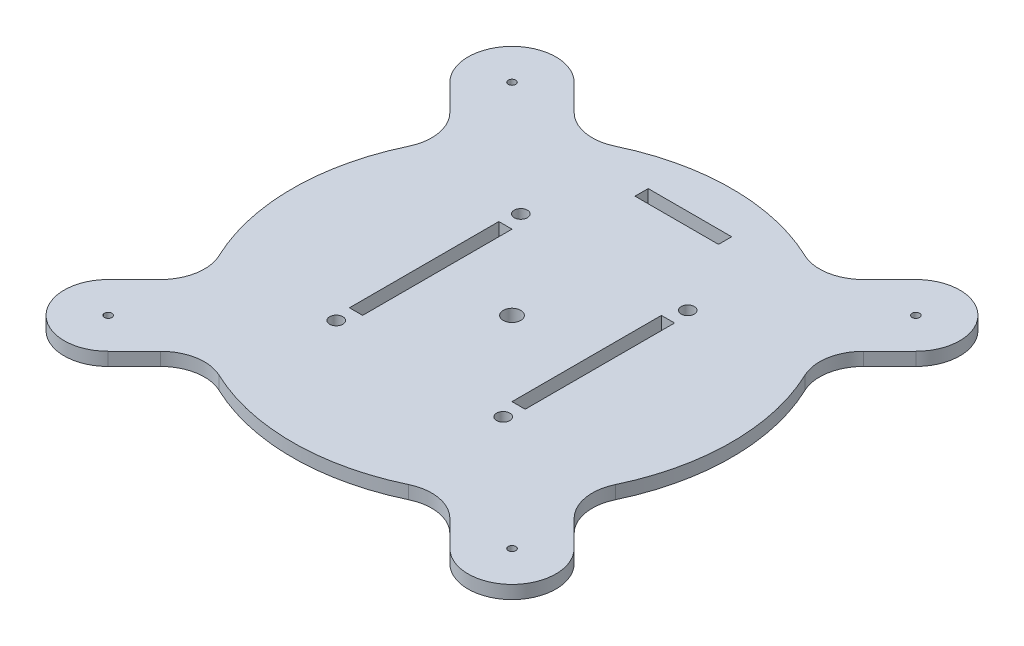
SolidWorks part; units mm, degrees
ref_plane "Plan de face" through (0, 0, 0) normal (0, 0, 1) x (1, 0, 0)
ref_plane "Plan de dessus" through (0, 0, 0) normal (0, 1, 0) x (1, 0, 0)
ref_plane "Plan de droite" through (0, 0, 0) normal (1, 0, 0) x (0, 0, -1)
sketch "Esquisse1" plane through (0, 0, 0) normal (0, 1, 0) x (1, 0, 0)
  line L0 (-45.9619, -45.9619) -> (0, 0) construction
  line L1 (0, 0) -> (-75, 0) construction
  line L2 (-45.9619, -45.9619) -> (-53.033, -53.033) construction
  line L3 (0, 0) -> (0, 75) construction
  line L4 (-38.8909, -53.033) -> (-27.5699, -41.7121)
  line L5 (-53.033, -38.8909) -> (-41.7121, -27.5699)
  line L6 (-38.8909, 53.033) -> (-27.5699, 41.7121)
  line L7 (-41.7121, 27.5699) -> (-53.033, 38.8909)
  line L8 (0, 0) -> (-45.9619, 45.9619) construction
  line L9 (0, 0) -> (45.9619, 45.9619) construction
  line L10 (0, 0) -> (45.9619, -45.9619) construction
  line L11 (27.5699, 41.7121) -> (38.8909, 53.033)
  line L12 (41.7121, 27.5699) -> (53.033, 38.8909)
  line L13 (27.5699, -41.7121) -> (38.8909, -53.033)
  line L14 (41.7121, -27.5699) -> (53.033, -38.8909)
  line L15 (-20, 17) -> (-17, 17)
  line L18 (-20, 17) -> (-20, -17)
  line L21 (-20, -17) -> (-17, -17)
  line L24 (-17, 17) -> (-17, -17)
  line L27 (-19, -21) -> (19, -21) construction
  line L28 (-19, -21) -> (-19, 21) construction
  line L29 (-19, 21) -> (19, 21) construction
  line L30 (19, -21) -> (19, 21) construction
  line L31 (-19, -21) -> (19, 21) construction
  line L32 (-19, 21) -> (19, -21) construction
  line L33 (20, -17) -> (17, -17)
  line L34 (17, 17) -> (17, -17)
  line L35 (20, 17) -> (17, 17)
  line L36 (20, 17) -> (20, -17)
  line L38 (-9.5, 40.5) -> (9.5, 40.5)
  line L39 (-9.5, 40.5) -> (-9.5, 37.5)
  line L40 (-9.5, 37.5) -> (9.5, 37.5)
  line L41 (9.5, 40.5) -> (9.5, 37.5)
  circle A0 centre (0, 0) radius 75 construction
  circle A1 centre (-45.9619, -45.9619) radius 0.85
  circle A2 centre (-45.9619, 45.9619) radius 0.85
  circle A3 centre (45.9619, 45.9619) radius 0.85
  circle A4 centre (45.9619, -45.9619) radius 0.85
  arc A9 (-27.5699, -41.7121) -> (27.5699, -41.7121) centre (0, 0) ccw
  arc A10 (-53.033, -38.8909) -> (-38.8909, -53.033) centre (-45.9619, -45.9619) ccw
  arc A11 (38.8909, -53.033) -> (53.033, -38.8909) centre (45.9619, -45.9619) ccw
  arc A12 (53.033, 38.8909) -> (38.8909, 53.033) centre (45.9619, 45.9619) ccw
  arc A13 (-38.8909, 53.033) -> (-53.033, 38.8909) centre (-45.9619, 45.9619) ccw
  arc A14 (-41.7121, 27.5699) -> (-41.7121, -27.5699) centre (0, 0) ccw
  arc A15 (27.5699, 41.7121) -> (-27.5699, 41.7121) centre (0, 0) ccw
  arc A16 (41.7121, -27.5699) -> (41.7121, 27.5699) centre (0, 0) ccw
  circle A25 centre (-19, 21) radius 1.5
  circle A26 centre (19, 21) radius 1.5
  circle A27 centre (19, -21) radius 1.5
  circle A28 centre (-19, -21) radius 1.5
  circle A29 centre (0, 0) radius 2
  point P15 (0, 0)
  point P23 (0, 0)
  point P43 (-20, 0)
  point P44 (-17, 0)
  point P55 (0, 37.5)
  point P70 (0, 0)
  dimension "D1" = 150
  dimension "D2" = 1.7
  dimension "D7" = 38
  dimension "D6" = 100
  dimension "D12" = 17
  dimension "D9" = 3
  dimension "D13" = 4
  dimension "D3" = 10
  dimension "D4" = 45
  dimension "D10" = 3
  dimension "D11" = 34
  dimension "D8" = 42
  dimension "D14" = 37.5
  dimension "D15" = 3
  dimension "D16" = 19
  dimension "D5" = 4
extrude "Boss.-Extru.1" add sketch "Esquisse1" along normal blind 3
fillet "Congé1" radius 10 8 edges at (-27.5699, 1.5, -41.7121) (27.5699, 1.5, -41.7121) (41.7121, 1.5, -27.5699) (41.7121, 1.5, 27.5699) (27.5699, 1.5, 41.7121) (-27.5699, 1.5, 41.7121) (-41.7121, 1.5, 27.5699) (-41.7121, 1.5, -27.5699)
